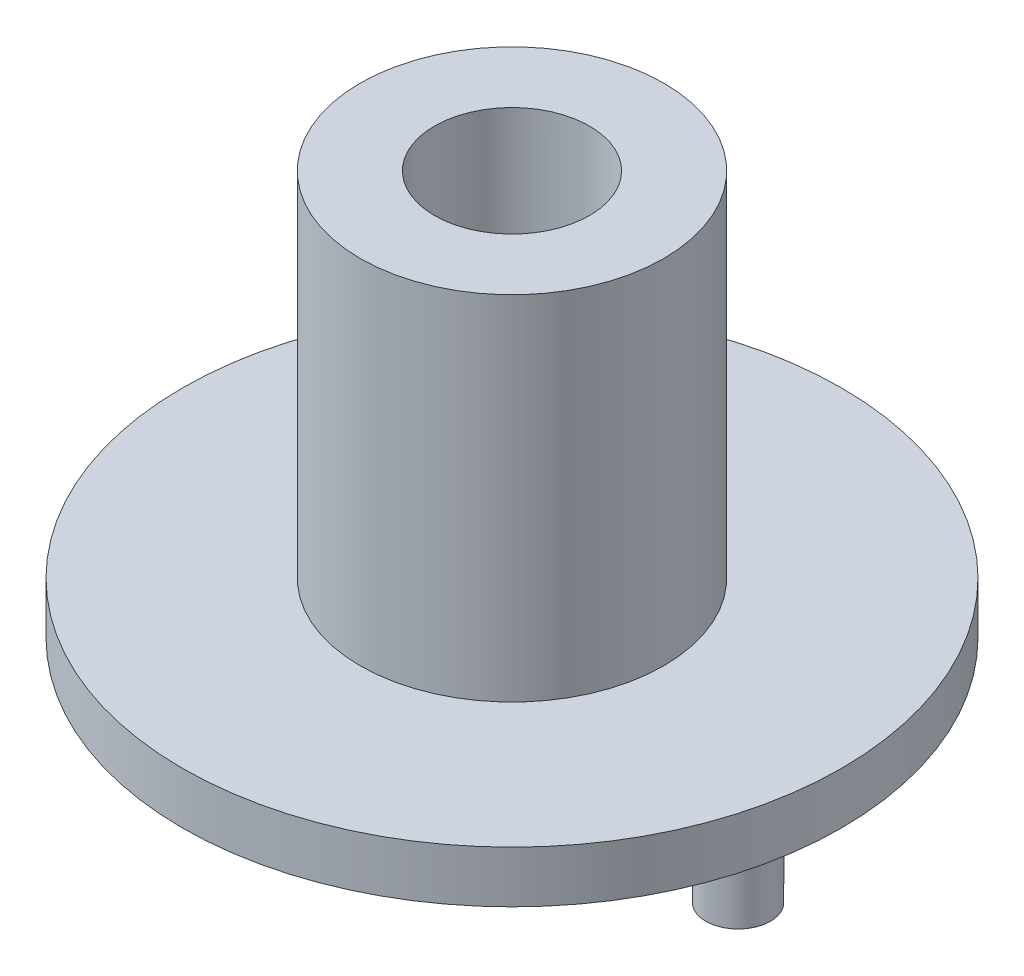
SolidWorks part; units mm, degrees
ref_plane "Спереди" through (0, 0, 0) normal (0, 0, 1) x (1, 0, 0)
ref_plane "Сверху" through (0, 0, 0) normal (0, 1, 0) x (1, 0, 0)
ref_plane "Справа" through (0, 0, 0) normal (1, 0, 0) x (0, 0, -1)
sketch "Эскиз1" plane through (0, 0, 0) normal (0, 1, 0) x (1, 0, 0)
  circle A0 centre (0, 0) radius 25.5
  circle A1 centre (0, 0) radius 6
  dimension "D1" = 51
  dimension "D2" = 12
extrude "Бобышка-Вытянуть1" add sketch "Эскиз1" along normal blind 4
sketch "Эскиз2" plane through (0, 4, 0) normal (0, 1, 0) x (1, 0, 0)
  circle A0 centre (0, 0) radius 6
  circle A1 centre (0, 0) radius 11.75
  dimension "D1" = 23.5
extrude "Бобышка-Вытянуть2" add sketch "Эскиз2" along normal blind 27.3
sketch "Эскиз3" plane through (0, 0, 0) normal (0, -1, 0) x (1, 0, 0)
  line L0 (0, 0) -> (0, 3.344) construction
  circle A0 centre (-17.5, 0) radius 2.5
  circle A1 centre (17.5, 0) radius 2.5
  dimension "D1" = 5
  dimension "D2" = 35
extrude "Бобышка-Вытянуть3" add sketch "Эскиз3" along normal blind 9
sketch "Эскиз5" plane through (0, 0, 0) normal (0, 0, 1) x (1, 0, 0)
  line L0 (6, 31.3) -> (-6, 31.3) construction
  circle A0 centre (0, 21.3) radius 3
  dimension "D1" = 6
  dimension "D2" = 10
extrude "Вырез-Вытянуть1" cut sketch "Эскиз5" against normal up to next
